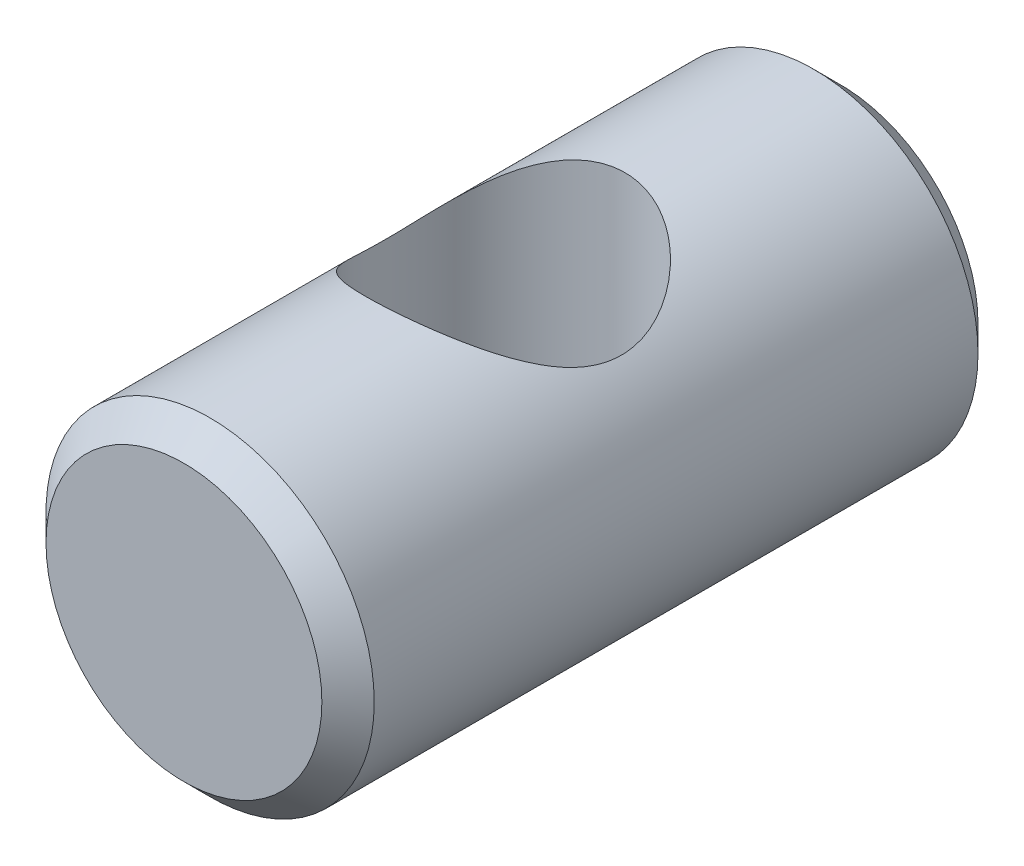
SolidWorks part; units mm, degrees
ref_plane "Front Plane" through (0, 0, 0) normal (0, 0, 1) x (1, 0, 0)
ref_plane "Top Plane" through (0, 0, 0) normal (0, 1, 0) x (1, 0, 0)
ref_plane "Right Plane" through (0, 0, 0) normal (1, 0, 0) x (0, 0, -1)
sketch "Sketch1" plane through (0, 0, 0) normal (0, 0, 1) x (1, 0, 0)
  circle A0 centre (0, 0) radius 4.765
  dimension "D1" = 9.53
extrude "Boss-Extrude1" add sketch "Sketch1" along normal mid plane 19.05
chamfer "Chamfer1" distance 0.76 angle 45 2 edges at (4.765, 0, -9.525) (4.765, 0, 9.525)
sketch "Sketch2" plane through (0, 0, 0) normal (0, 1, 0) x (1, 0, 0)
  circle A0 centre (-0.25, 0) radius 3.43
  dimension "D2" = 6.86
  dimension "D1" = 0.25
extrude "Cut-Extrude1" cut sketch "Sketch2" against normal through all both and the other way through all
